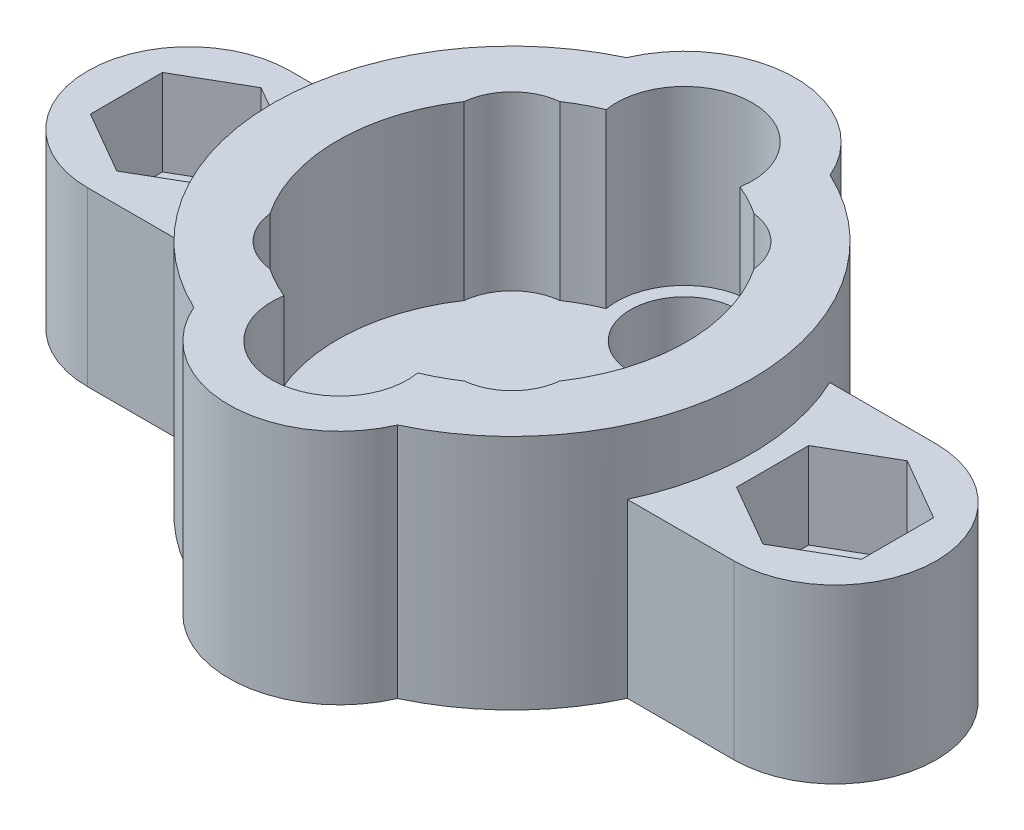
SolidWorks part; units mm, degrees
ref_plane "Front Plane" through (0, 0, 0) normal (0, 0, 1) x (1, 0, 0)
ref_plane "Top Plane" through (0, 0, 0) normal (0, 1, 0) x (1, 0, 0)
ref_plane "Right Plane" through (0, 0, 0) normal (1, 0, 0) x (0, 0, -1)
sketch "Sketch1" plane through (0, 0, 0) normal (0, 1, 0) x (1, 0, 0)
  line L0 (0, 0) -> (0, 8) construction
  line L1 (0, 0) -> (0, -8) construction
  circle A0 centre (0, 0) radius 8.1
  circle A1 centre (0, 8) radius 2.5
  circle A2 centre (0, -8) radius 2.5
  circle A3 centre (0, -8) radius 3.15
  circle A4 centre (0, 8) radius 3.15
  circle A5 centre (0, 0) radius 11.1
  circle A6 centre (0, 8) radius 5.15
  circle A7 centre (0, -8) radius 5.15
  dimension "D1" = 16.2
  dimension "D4" = 5
  dimension "D5" = 6.3
  dimension "D6" = 5
  dimension "D7" = 6.3
  dimension "D8" = 3
  dimension "D9" = 2
  dimension "D10" = 2
  dimension "D2" = 8
  dimension "D3" = 8
extrude "Boss-Extrude1" add sketch "Sketch1" along normal blind 3 contours A5 A6 | A0 A6 A5 A4 | A0 A4 A1 | A5 A6 A0 A4 | A7 A0 A6 A5 | A0 A4 A1 | A0 A6 A4 | A7 A5 A6 A0 | A7 A0 A6 | A0 A7 A3 | A0 A3 A2 | A0 A3 A2 | A5 A7 A0 A3 | A5 A7 | A0 A7 A5 A3 | A5 A4 | A5 A3
sketch "Sketch3" plane through (0, 3, 0) normal (0, 1, 0) x (1, 0, 0)
  line L0 (0, 0) -> (0, 8) construction
  line L1 (0, 0) -> (0, -8) construction
  circle A0 centre (0, 0) radius 8.1
  circle A1 centre (0, 8) radius 3.15
  circle A2 centre (0, -8) radius 3.15
  circle A3 centre (0, 8) radius 5.15
  circle A4 centre (0, -8) radius 5.15
  circle A5 centre (0, 0) radius 11.1
  arc A6 (4.7274, 10.043) -> (-4.7274, 10.043) centre (0, 8) ccw construction
  arc A7 (-4.7274, -10.043) -> (4.7274, -10.043) centre (0, -8) ccw construction
  arc M6 (-4.7274, 10.043) -> (-4.7274, -10.043) centre (0, 0) ccw
  arc M7 (-4.7274, -10.043) -> (4.7274, -10.043) centre (0, -8) ccw
  arc M8 (4.7274, -10.043) -> (4.7274, 10.043) centre (0, 0) ccw
  arc M9 (4.7274, 10.043) -> (-4.7274, 10.043) centre (0, 8) ccw
  dimension "D1" = 16.2
  dimension "D4" = 6.3
  dimension "D5" = 6.3
  dimension "D6" = 0
  dimension "D7" = 0
  dimension "D2" = 8
  dimension "D3" = 8
extrude "Boss-Extrude2" add sketch "Sketch3" along normal blind 8 contours A5 M9 | A5 M7 | A4 A0 A3 M6 | A4 A5 A2 A0 | A2 A5 A4 A0 | A4 A3 A0 M8 | A3 A5 A1 A0 | A1 A5 A3 A0
sketch "Sketch4" plane through (0, 0, 0) normal (0, -1, 0) x (1, 0, 0)
  line L0 (0, 0) -> (15, 0) construction
  line L1 (0, 0) -> (-15, 0) construction
  line L2 (-15, 4.7) -> (-10.0558, 4.7)
  line L3 (-15, -4.7) -> (-10.0558, -4.7)
  line L4 (15, -4.7) -> (10.0558, -4.7)
  line L5 (15, 4.7) -> (10.0558, 4.7)
  circle A0 centre (-15, 0) radius 1.7
  circle A1 centre (15, 0) radius 1.7
  circle A2 centre (-15, 0) radius 4.7
  circle A3 centre (15, 0) radius 4.7
  arc A4 (-4.7274, 10.043) -> (-4.7274, -10.043) centre (0, 0) ccw construction
  arc M5 (-4.7274, 10.043) -> (-4.7274, -10.043) centre (0, 0) ccw
  arc M7 (4.7274, -10.043) -> (4.7274, 10.043) centre (0, 0) ccw
  dimension "D3" = 3.4
  dimension "D4" = 3.4
  dimension "D5" = 3
  dimension "D6" = 3
  dimension "D1" = 15
  dimension "D2" = 15
extrude "Boss-Extrude3" add sketch "Sketch4" against normal blind 8 contours A3 L4 M7 | A3 L5 M7 | A3 A1 M7 | A2 A0 M5 | A2 L3 M5 | A2 L2 M5 | A2 M5 | A3 M7
sketch "Sketch5" plane through (0, 8, 0) normal (0, 1, 0) x (1, 0, 0)
  line L1 (-15, -3.3486) -> (-12.1, -1.6743)
  line L2 (-12.1, -1.6743) -> (-12.1, 1.6743)
  line L3 (-12.1, 1.6743) -> (-15, 3.3486)
  line L4 (-15, 3.3486) -> (-17.9, 1.6743)
  line L5 (-17.9, 1.6743) -> (-17.9, -1.6743)
  line L6 (-17.9, -1.6743) -> (-15, -3.3486)
  line L7 (15, -3.3486) -> (17.9, -1.6743)
  line L8 (17.9, -1.6743) -> (17.9, 1.6743)
  line L9 (17.9, 1.6743) -> (15, 3.3486)
  line L10 (15, 3.3486) -> (12.1, 1.6743)
  line L11 (12.1, 1.6743) -> (12.1, -1.6743)
  line L12 (12.1, -1.6743) -> (15, -3.3486)
  circle A0 centre (-15, 0) radius 2.9 construction
  circle A1 centre (15, 0) radius 2.9 construction
  dimension "D1" = 5.8
  dimension "D2" = 5.8
extrude "Cut-Extrude1" cut sketch "Sketch5" against normal blind 4
sketch "Sketch6" plane through (0, 0, 0) normal (0, -1, 0) x (1, 0, 0)
  line L0 (0, 0) -> (15, 0) construction
  line L1 (0, 0) -> (-15, 0) construction
sketch "Sketch7" plane through (0, 3, 0) normal (0, 1, 0) x (1, 0, 0)
  line L0 (0, 13.15) -> (0, -13.15) construction
  line L1 (-4.2426, 4.2426) -> (4.2426, -4.2426)
  line L2 (-4.2426, -4.2426) -> (4.2426, 4.2426)
  arc A0 (4.7274, 10.043) -> (-4.7274, 10.043) centre (0, 8) ccw construction
  arc A1 (-4.7274, -10.043) -> (4.7274, -10.043) centre (0, -8) ccw construction
  circle A2 centre (4.2426, 4.2426) radius 2.5
  circle A3 centre (4.2426, -4.2426) radius 2.5
  circle A4 centre (-4.2426, -4.2426) radius 2.5
  circle A5 centre (-4.2426, 4.2426) radius 2.5
  point P13 (0, 0)
  point P16 (0, 0)
  dimension "D6" = 5
  dimension "D7" = 5
  dimension "D8" = 5
  dimension "D9" = 5
  dimension "D1" = 12
  dimension "D2" = 12
  dimension "D3" = 90
  dimension "D4" = 45
  dimension "D5" = 45
extrude "Cut-Extrude2" cut sketch "Sketch7" along normal blind 10
